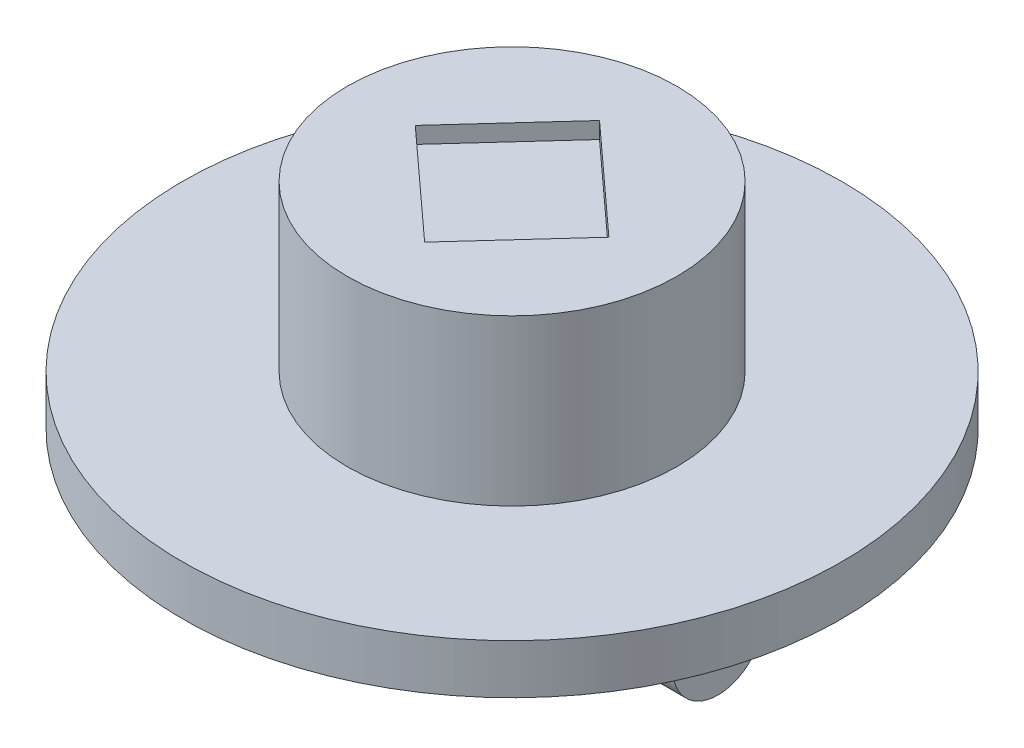
SolidWorks part; units mm, degrees
ref_plane "Front Plane" through (0, 0, 0) normal (0, 0, 1) x (1, 0, 0)
ref_plane "Top Plane" through (0, 0, 0) normal (0, 1, 0) x (1, 0, 0)
ref_plane "Right Plane" through (0, 0, 0) normal (1, 0, 0) x (0, 0, -1)
sketch "Sketch1" plane through (0, 0, 0) normal (0, 1, 0) x (1, 0, 0)
  circle A0 centre (0, 0) radius 50.8
  dimension "D1" = 101.6
extrude "Boss-Extrude1" add sketch "Sketch1" along normal blind 7.62
sketch "Sketch2" plane through (0, 0, 0) normal (0, -1, 0) x (1, 0, 0)
  line L1 (-31.75, -6.985) -> (-26.67, -6.985)
  line L2 (-31.75, -6.985) -> (-31.75, 6.985)
  line L3 (-31.75, 6.985) -> (-26.67, 6.985)
  line L4 (-26.67, -6.985) -> (-26.67, 6.985)
  line L5 (-31.75, -6.985) -> (-26.67, 6.985) construction
  line L6 (-31.75, 6.985) -> (-26.67, -6.985) construction
  point P0 (-29.21, 0)
  dimension "D1" = 29.21
  dimension "D2" = 5.08
  dimension "D3" = 13.97
extrude "Boss-Extrude2" add sketch "Sketch2" along normal blind 12.7
sketch "Sketch3" plane through (-31.75, 0, 0) normal (-1, 0, 0) x (0, 0, 1)
  line L0 (6.985, -12.7) -> (-6.985, -12.7) construction
  circle A0 centre (0, -12.7) radius 6.985
extrude "Boss-Extrude3" add sketch "Sketch3" against normal blind 5.08
sketch "Sketch4" plane through (-31.75, 0, 0) normal (-1, 0, 0) x (0, 0, 1)
  circle A0 centre (0, -12.7) radius 2.5161
  dimension "D1" = 5.0322
extrude "Cut-Extrude1" cut sketch "Sketch4" against normal blind 5.08
sketch "Sketch5" plane through (0, 0, 0) normal (0, -1, 0) x (1, 0, 0)
  line L1 (26.67, -6.985) -> (31.75, -6.985)
  line L2 (26.67, -6.985) -> (26.67, 6.985)
  line L3 (26.67, 6.985) -> (31.75, 6.985)
  line L4 (31.75, -6.985) -> (31.75, 6.985)
  line L5 (26.67, -6.985) -> (31.75, 6.985) construction
  line L6 (26.67, 6.985) -> (31.75, -6.985) construction
  point P0 (29.21, 0)
  dimension "D1" = 29.21
  dimension "D2" = 13.97
  dimension "D3" = 5.08
extrude "Boss-Extrude4" add sketch "Sketch5" along normal blind 12.7
sketch "Sketch6" plane through (31.75, 0, 0) normal (1, 0, 0) x (0, 0, -1)
  line L0 (6.985, -12.7) -> (-6.985, -12.7) construction
  circle A0 centre (0, -12.7) radius 6.985
  dimension "D1" = 13.97
extrude "Boss-Extrude5" add sketch "Sketch6" against normal blind 5.08
sketch "Sketch8" plane through (31.75, 0, 0) normal (1, 0, 0) x (0, 0, -1)
  line L0 (6.985, 0) -> (-6.985, 0) construction
  circle A0 centre (0, -12.7) radius 2.54
  point P2 (0, 0)
  dimension "D2" = 5.08
  dimension "D1" = 12.7
extrude "Cut-Extrude2" cut sketch "Sketch8" against normal blind 5.08
sketch "Sketch9" plane through (0, 7.62, 0) normal (0, 1, 0) x (1, 0, 0)
  circle A0 centre (0, 0) radius 25.4
  dimension "D1" = 50.8
extrude "Boss-Extrude6" add sketch "Sketch9" along normal blind 25.4
sketch "Sketch10" plane through (0, 33.02, 0) normal (0, 1, 0) x (1, 0, 0)
  line L0 (1.3787, -14.8587) -> (-14.9225, 0)
  line L1 (1.3787, -14.8587) -> (14.9225, 0)
  line L2 (-14.9225, 0) -> (-1.3787, 14.8587)
  line L3 (14.9225, 0) -> (-1.3787, 14.8587)
  line L4 (1.3787, -14.8587) -> (-1.3787, 14.8587) construction
  line L5 (-14.9225, 0) -> (14.9225, 0) construction
  point P1 (0, 0)
  dimension "D1" = 29.845
  dimension "D2" = 29.845
extrude "Cut-Extrude3" cut sketch "Sketch10" against normal blind 2.54
